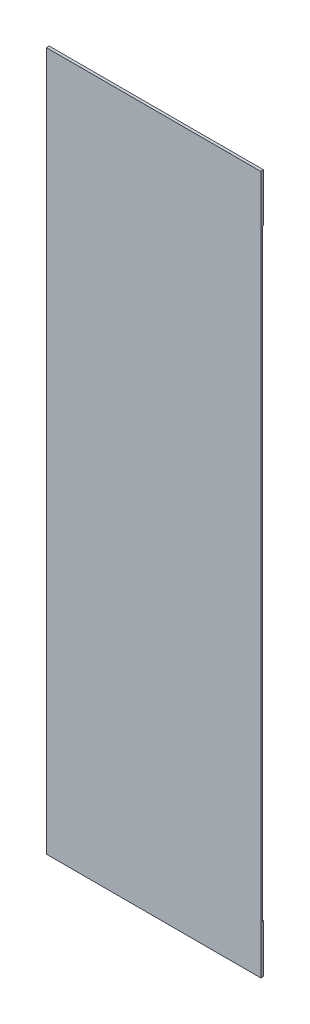
SolidWorks part; units mm, degrees
ref_plane "Front Plane" through (0, 0, 0) normal (0, 0, 1) x (1, 0, 0)
ref_plane "Top Plane" through (0, 0, 0) normal (0, 1, 0) x (1, 0, 0)
ref_plane "Right Plane" through (0, 0, 0) normal (1, 0, 0) x (0, 0, -1)
sketch "Sketch2" plane through (0, 0, 0) normal (1, 0, 0) x (0, 0, -1)
  line L0 (0, 0) -> (50000, 0) construction
  line L1 (-8.7551, 50.8) -> (49991.2449, 50.8) construction
  line L2 (0, -1000) -> (0, 49000) construction
  line L3 (1001.3589, 47.3) -> (0.1, 47.3) construction
  line L4 (1000.2, 3.5) -> (0.1, 3.5) construction
  line L5 (0.1, -946.5991) -> (0.1, 0) construction
  line L6 (0.2, -950.3099) -> (0.2, 49049.6901) construction
  line L7 (0.2, 47.3) -> (0.1, 47.3)
  line L8 (0, 50.8) -> (0.2, 50.8)
  line L9 (0, 50.8) -> (0, 47.3)
  line L10 (0.1, 47.3) -> (0.1, 3.5)
  line L11 (0.2, 50.8) -> (0.2, 47.3)
  line L12 (0, 0) -> (0.2, 0)
  line L13 (0, 0) -> (0, 3.5)
  line L14 (0.1, 3.5) -> (0.2, 3.5)
  line L15 (0.2, 0) -> (0.2, 3.5)
  line L16 (0, 3.5) -> (-50000, 3.5) construction
  line L17 (0, 3.5) -> (0, 47.3)
  line L18 (0.1, 3.5) -> (0.1, 47.3) construction
  line L19 (0, 47.3) -> (-49998.6411, 47.3) construction
  line L20 (0.1, 50.8) -> (0.1, 49053.4009) construction
  dimension "D4" = 0.2
  dimension "D5" = 0.1
  dimension "D3" = 3.5
  dimension "D2" = 3.5
  dimension "D1" = 50.8
extrude "Boss-Extrude1" add sketch "Sketch2" against normal blind 15.6
sketch "Sketch3" plane through (0, 0, 0) normal (1, 0, 0) x (0, 0, -1)
  line L0 (-1000.1029, 42.6938) -> (48999.8971, 42.6938) construction
equation "\"D1@Boss-Extrude1\"=.3*52mm"
